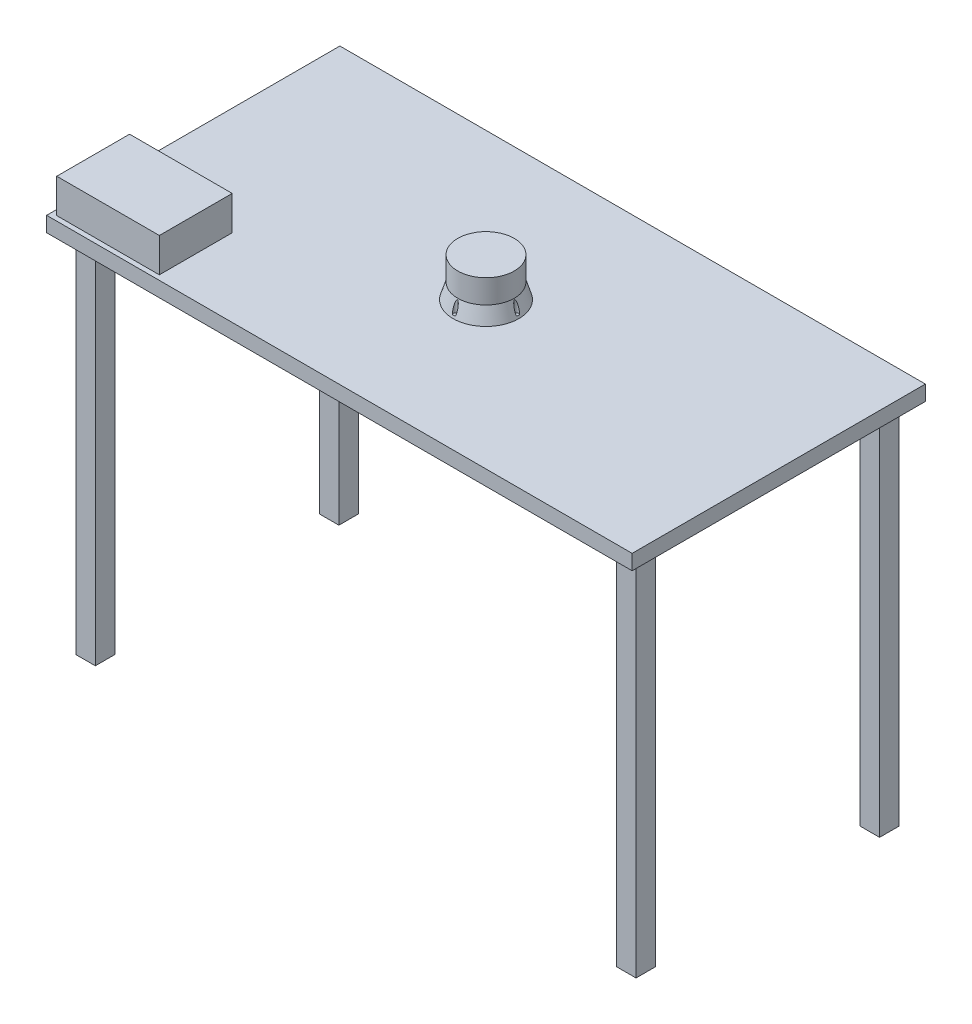
SolidWorks part; units mm, degrees
ref_plane "Alzado" through (0, 0, 0) normal (0, 0, 1) x (1, 0, 0)
ref_plane "Planta" through (0, 0, 0) normal (0, 1, 0) x (1, 0, 0)
ref_plane "Vista lateral" through (0, 0, 0) normal (1, 0, 0) x (0, 0, -1)
sketch "Croquis1" plane through (0, 0, 0) normal (0, 0, 1) x (1, 0, 0)
  line L0 (0, 0) -> (0, 80)
  line L1 (0, 80) -> (-58, 80)
  line L2 (-58, 80) -> (-58, 31.4551)
  line L3 (-58, 31.4551) -> (-67.5, 0)
  line L4 (-67.5, 0) -> (0, 0)
  dimension "D1" = 80
  dimension "D2" = 67.5
  dimension "D3" = 58
revolve "Revolución1" add sketch "Croquis1" angle 360 about L0
sketch "Croquis2" plane through (0, 80, 0) normal (0, 1, 0) x (1, 0, 0)
  circle A0 centre (0, 63.0252) radius 4.3246
  circle A1 centre (63.0252, 0) radius 4.3246
  circle A2 centre (0, -63.0252) radius 4.3246
  circle A3 centre (-63.0252, 0) radius 4.3246
  point P11 (0, 0)
  dimension "D1" = 4
extrude "Cortar-Extruir1" cut sketch "Croquis2" against normal blind 25 from offset 50 offset against normal yes
sketch "Croquis3" plane through (0, 0, 0) normal (0, -1, 0) x (1, 0, 0)
  line L1 (-601, 301) -> (601, 301)
  line L2 (-601, 301) -> (-601, -301)
  line L3 (-601, -301) -> (601, -301)
  line L4 (601, 301) -> (601, -301)
  line L5 (-601, 301) -> (601, -301) construction
  line L6 (-601, -301) -> (601, 301) construction
  point P0 (0, 0)
  dimension "D1" = 602
  dimension "D2" = 1202
extrude "Saliente-Extruir1" add sketch "Croquis3" along normal blind 31
sketch "Croquis4" plane through (0, -31, 0) normal (0, -1, 0) x (1, 0, 0)
  line L0 (601, 301) -> (-601, 301) construction
  line L1 (-571, 271) -> (-531, 271)
  line L2 (-571, 271) -> (-571, 231)
  line L3 (-571, 231) -> (-531, 231)
  line L4 (-531, 271) -> (-531, 231)
  line L5 (-601, 301) -> (-601, -301) construction
  line L6 (539, 271) -> (539, 231)
  line L7 (539, 271) -> (579, 271)
  line L8 (579, 271) -> (579, 231)
  line L9 (539, 231) -> (579, 231)
  line L10 (539, -229) -> (539, -269)
  line L11 (539, -229) -> (579, -229)
  line L12 (579, -229) -> (579, -269)
  line L13 (539, -269) -> (579, -269)
  line L14 (-571, -229) -> (-571, -269)
  line L15 (-571, -229) -> (-531, -229)
  line L16 (-531, -229) -> (-531, -269)
  line L17 (-571, -269) -> (-531, -269)
  dimension "D1" = 40
  dimension "D2" = 40
  dimension "D3" = 30
  dimension "D4" = 30
  dimension "D5" = 2
  dimension "D6" = 2
extrude "Saliente-Extruir2" add sketch "Croquis4" along normal blind 750
sketch "Croquis5" plane through (0, 0, 0) normal (0, 1, 0) x (1, 0, 0)
  line L1 (-590.0955, -291.1417) -> (-379.4399, -291.1417)
  line L2 (-590.0955, -291.1417) -> (-590.0955, -141.6022)
  line L3 (-590.0955, -141.6022) -> (-379.4399, -141.6022)
  line L4 (-379.4399, -291.1417) -> (-379.4399, -141.6022)
extrude "Saliente-Extruir3" add sketch "Croquis5" along normal blind 70
